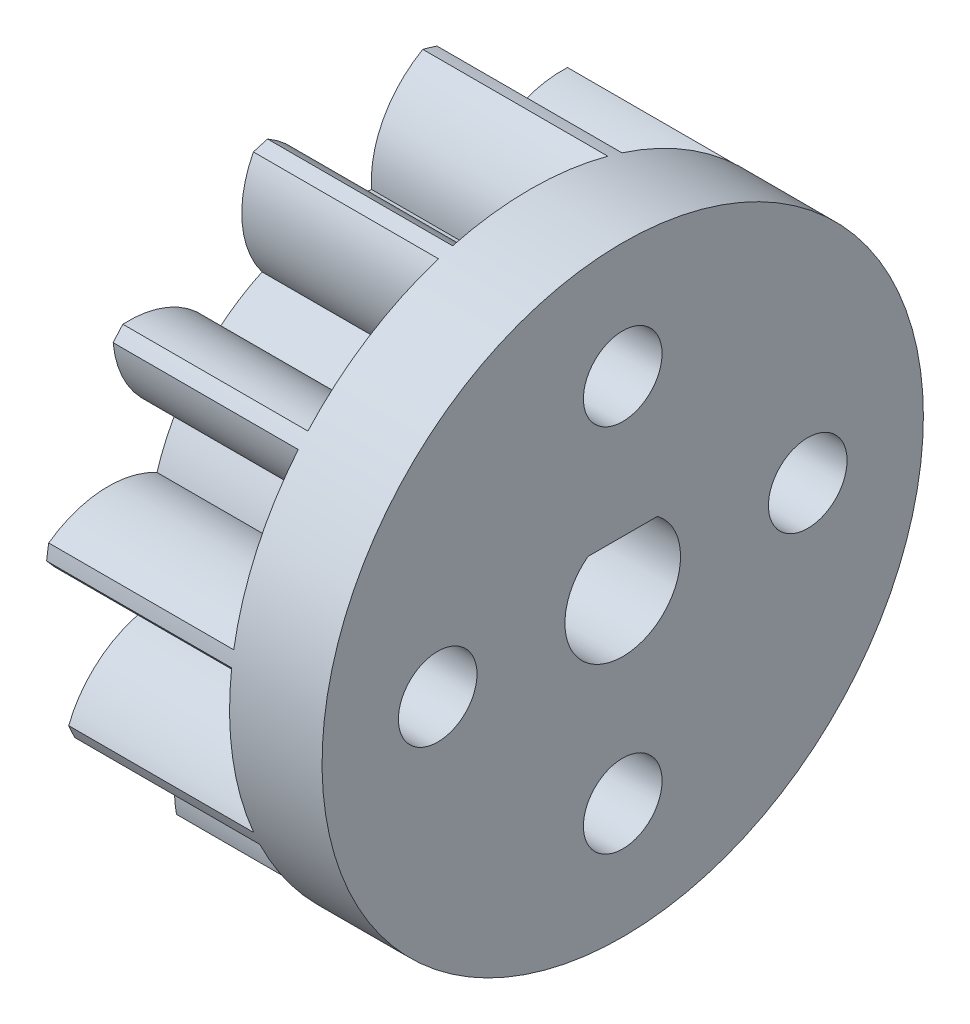
SolidWorks part; units mm, degrees
ref_plane "Plane1" through (0, 0, 0) normal (0, 0, 1) x (1, 0, 0)
ref_plane "Plane2" through (0, 0, 0) normal (0, 1, 0) x (1, 0, 0)
ref_plane "Plane3" through (0, 0, 0) normal (1, 0, 0) x (0, 0, -1)
sketch "HoldingSke" plane through (0, 0, 0) normal (0, 1, 0) x (1, 0, 0)
  line L0 (0, 0) -> (0.4908, -0.0954)
  line L1 (-15, 0) -> (100, 0) construction
  line L2 (0, 0) -> (-2.1039, 2.3779)
  line L3 (0, 0) -> (-11.863, 4.5341)
  line L4 (0, 0) -> (8.4773, 1.6478)
  line L5 (0, 0) -> (-46.8476, -17.4728)
  line L6 (0, 0) -> (-6.6317, -4.4744)
  line L7 (-2.1039, 2.3779) -> (8.6586, 51.2059)
  line L8 (-76.2, 54.61) -> (-76.1, 54.61)
  line L9 (-71.009, 38.7566) -> (-53.1078, 45.2721)
  line L10 (-76.2, 71.12) -> (104.1128, 71.12)
  line L11 (0, 0) -> (-8, 0)
  line L12 (-76.2, 101.6) -> (-76.133, 101.6)
  line L13 (24.9733, 27.94) -> (52.9518, 28.4284)
  line L14 (24.9733, 27.94) -> (24.9743, 27.94)
  line L15 (24.9733, 27.94) -> (100.4006, 29.5858)
  line L16 (-63.627, -2) -> (-12.827, -2)
  circle A0 centre (0, 0) radius 0.4
  circle A1 centre (0, 0) radius 8.499
  circle A2 centre (0, 0) radius 37.5
  circle A3 centre (0, 0) radius 0.4
  dimension "MHD" = 16.998
  dimension "Hub_dia" = 75
  dimension "Bore" = 0.8
  dimension "MBD" = 0.8
  dimension "Num_teeth" = 11
  dimension "Pitch" = 0.5
  dimension "Overall_len" = 50
  dimension "Show_teeth" = 11
  dimension "Thickness" = 8
  dimension "OAL" = 50.0001
  dimension "T_dim" = 0.1
  dimension "Ap" = 20
  dimension "H" = 19.05
  dimension "Pitch_radius" = 180.3128
  dimension "Width" = 8
  dimension "Backlash" = 0.067
  dimension "Addendum_fac" = 1
  dimension "Dedendum_fac" = 1.25
  dimension "Clearance_fac" = 0.25
  dimension "Dedendum_add" = 0.001
  dimension "Module" = 2
sketch "BasProSke" plane through (0, 0, 0) normal (0, 1, 0) x (1, 0, 0)
  line L0 (-10, 0) -> (60, 0) construction
  line L1 (0, 0) -> (0, 13)
  line L2 (0, 0) -> (8, 0)
  line L3 (8, 0) -> (8, 13)
  line L4 (8, 13) -> (0, 13)
  dimension "Thickness" = 8
  dimension "Diameter" = 26
revolve "Base-Revolve" add sketch "BasProSke" angle 360 about L0
sketch "TooCutSke" plane through (0, 0, 0) normal (1, 0, 0) x (0, 0, -1)
  line L1 (0, 0) -> (0, 107) construction
  line L2 (0, 0) -> (-1.6825, 10.8706) construction
  line L3 (0, 0) -> (-6.1442, 20.9251) construction
  line L4 (-1.6825, 10.8706) -> (-3.0721, 10.4626) construction
  arc A0 (1.1399, 8.4222) -> (-1.1399, 8.4222) centre (0, 0) ccw
  arc A1 (3.3871, 12.5773) -> (-3.3871, 12.5773) centre (0, 0) ccw
  circle A2 centre (0, 0) radius 11 construction
  circle A3 centre (0, 0) radius 10.3366 construction
  arc A4 (-1.1399, 8.4222) -> (-3.3871, 12.5773) centre (-5.5288, 8.7337) ccw
  arc A5 (3.3871, 12.5773) -> (1.1399, 8.4222) centre (5.5288, 8.7337) ccw
  dimension "Root_dia" = 16.998
  dimension "Overcut_dia" = 26.0508
  dimension "Pitch_dia" = 22
  dimension "Base_dia" = 20.6732
  dimension "Flank_rad" = 4.4
  dimension "Half_ang" = 16.364
  dimension "Half_CT" = 1.4482
extrude "ToothCut" cut sketch "TooCutSke" along normal through all
fillet "Breaks" [suppressed] radius 0.04
fillet "RootFillets" [suppressed] radius 0.501
pattern_circular "TeethCuts" count 11 every 32.727 about axis through (-10, 0, 0) along (1, 0, 0) of "ToothCut", "RootFillets", "Breaks"
sketch "HubNeaOneSke" plane through (0, 0, 0) normal (-1, 0, 0) x (0, 0, 1)
  circle A0 centre (0, 0) radius 8.499
  dimension "Diameter" = 16.998
extrude "HubNearOne" [suppressed] add sketch "HubNeaOneSke" along normal blind 42.0001
sketch "HubNeaBotSke" plane through (0, 0, 0) normal (-1, 0, 0) x (0, 0, 1)
  circle A0 centre (0, 0) radius 8.499
  dimension "Diameter" = 16.998
extrude "HubNearBoth" [suppressed] add sketch "HubNeaBotSke" along normal blind 21
ref_plane "FarPln" through (8, 0, 0) normal (1, 0, 0) x (0, 0, -1)
sketch "HubFarSke" plane through (8, 0, 0) normal (1, 0, 0) x (0, 0, -1)
  circle A0 centre (0, 0) radius 8.499
  dimension "Diameter" = 16.998
extrude "HubFar" [suppressed] add sketch "HubFarSke" along normal blind 21
sketch "BorSke" plane through (0, 0, 0) normal (1, 0, 0) x (0, 0, -1)
  circle A0 centre (0, 0) radius 0.4
  dimension "Diameter" = 0.8
extrude "Bore" cut sketch "BorSke" along normal mid plane 100.0001
sketch "KeySke" plane through (0, 0, 0) normal (1, 0, 0) x (0, 0, -1)
  line L0 (-0.05, 0) -> (-0.05, 0.5)
  line L1 (-0.05, 0.5) -> (0.05, 0.5)
  line L2 (0.05, 0.5) -> (0.05, 0)
  line L3 (0, 0) -> (0, 34) construction
  line L4 (-0.05, 0) -> (0.05, 0)
  dimension "Offset" = 0.5
  dimension "Width" = 0.1
extrude "Keyway" [suppressed] cut sketch "KeySke" along normal mid plane 100.0001
pattern_circular "Keyway2" [suppressed] count 2 every 90 about axis through (-10, 0, 0) along (1, 0, 0)
sketch "Schizzo2" plane through (8, 0, 0) normal (1, 0, 0) x (0, 0, -1)
  circle A0 centre (0, 0) radius 13
  dimension "D1" = 26
extrude "Estrusione-Estrusione1" add sketch "Schizzo2" along normal blind 4
sketch "Schizzo1" plane through (12, 0, 0) normal (1, 0, 0) x (0, 0, -1)
  line L0 (-1.5, 2) -> (1.5, 2)
  arc A0 (-1.5, 2) -> (1.5, 2) centre (0, 0) ccw
  dimension "D1" = 5
  dimension "D2" = 2
extrude "Taglio-Estrusione1" cut sketch "Schizzo1" against normal blind 14
hole_wizard "Foro per Vite M3-1" positions "Schizzo3" profile "Schizzo4" hole size "M3" standard "DIN"
sketch "Schizzo3" plane through (12, 0, 0) normal (1, 0, 0) x (0, 0, -1)
  circle A0 centre (0, 0) radius 8 construction
  point P3 (0, 8)
  point P5 (8, 0)
  point P7 (0, -8)
  point P9 (-8, 0)
  dimension "D1" = 16
sketch "Schizzo4" plane through (12, 8, 0) normal (0, 1, 0) x (0, 0, -1)
  line L0 (0, 0) -> (0, 4.0215)
  line L1 (0, 4.0215) -> (1.7, 3)
  line L2 (1.7, 3) -> (1.7, 0)
  line L5 (1.7, 0) -> (0, 0)
  line L10 (0, 4.0215) -> (-1.7, 3) construction
  line L11 (0, -6.35) -> (0, 107.95) construction
  dimension "Hole Dia." = 3.4
  dimension "Hole Depth" = 3
  dimension "Drill Angle" = 118
equation "' \"Module@HoldingSke\" = 6.35"
equation "' \"Num_teeth@HoldingSke\" = 12"
equation "' \"Ap@HoldingSke\" =  20"
equation "' \"Ap@HoldingSke\" = 20"
equation "' \"Width@HoldingSke\" = 0.5 * 25.4"
equation "' \"Hub_dia@HoldingSke\"= 1 * 25.4"
equation "' \"Hub_dia@HoldingSke\" = 1 * 25.4"
equation "' \"Overall_len@HoldingSke\" = 1.0 * 25.4"
equation "' \"Bore@HoldingSke\" = 0.75 * 25.4"
equation "' \"T_dim@HoldingSke\" = 0.1 * 25.4"
equation "' \"Width@KeySke\" = 0.25 * 25.4"
equation "' \"Show_teeth@HoldingSke\" = 13"
equation "' \"Backlash@HoldingSke\" = 0.009 * 25.4"
equation "' \"Addendum_fac@HoldingSke\" = 1.0"
equation "' \"Dedendum_fac@HoldingSke\" = 1.25"
equation "' \"Dedendum_add@HoldingSke\" = 0.00005 * 25.4"
equation "' \"Clearance_fac@HoldingSke\" = 0.25"
equation "\"Pitch@HoldingSke\" = 1 / \"Module@HoldingSke\""
equation "\"Overcut_dia@TooCutSke\" = (\"Num_teeth@HoldingSke\" + 2 * \"Addendum_fac@HoldingSke\") / \"Pitch@HoldingSke\" + 0.002 * 25.4"
equation "\"Pitch_dia@TooCutSke\" = \"Num_teeth@HoldingSke\" / \"Pitch@HoldingSke\""
equation "\"Base_dia@TooCutSke\" = \"Num_teeth@HoldingSke\" / \"Pitch@HoldingSke\" * cos((\"Ap@HoldingSke\"  * 3.14159265 / 180))"
equation "\"Root_dia@TooCutSke\" = (\"Num_teeth@HoldingSke\" + 2) / \"Pitch@HoldingSke\" - 2 * (\"Addendum_fac@HoldingSke\" + \"Dedendum_fac@HoldingSke\") / \"Pitch@HoldingSke\" - \"Dedendum_add@HoldingSke\" * 2"
equation "\"Half_ang@TooCutSke\" = 180 / \"Num_teeth@HoldingSke\""
equation "\"Half_CT@TooCutSke\" = \"Num_teeth@HoldingSke\" / \"Pitch@HoldingSke\" * sin((3.14159265 / 2 / \"Num_teeth@HoldingSke\")) / 2 - 7 * \"Backlash@HoldingSke\" / 4"
equation "\"Flank_rad@TooCutSke\" = \"Num_teeth@HoldingSke\" / \"Pitch@HoldingSke\" / 5"
equation "\"Radius@RootFillets\" = \"Clearance_fac@HoldingSke\" / \"Pitch@HoldingSke\" + \"Dedendum_add@HoldingSke\""
equation "\"Break_rad@Breaks\" = 0.02 / \"Pitch@HoldingSke\""
equation "\"Thickness@HoldingSke\" = \"Width@HoldingSke\""
equation "\"OAL@HoldingSke\" = \"Thickness@HoldingSke\""
equation "\"MHD@HoldingSke\" = (\"Num_teeth@HoldingSke\" + 2) / \"Pitch@HoldingSke\" - 2 * (\"Addendum_fac@HoldingSke\" + \"Dedendum_fac@HoldingSke\")  / \"Pitch@HoldingSke\" - \"Dedendum_add@HoldingSke\" * 2"
equation "\"MBD@HoldingSke\" = (\"Num_teeth@HoldingSke\" + 2) / \"Pitch@HoldingSke\" - 2 * (\"Addendum_fac@HoldingSke\" + \"Dedendum_fac@HoldingSke\")  / \"Pitch@HoldingSke\" - \"Dedendum_add@HoldingSke\" * 2 - 0.002 * 25.4"
equation "\"MHD@HoldingSke\" = ((sgn( \"MHD@HoldingSke\" - \"Hub_dia@HoldingSke\" )-1)*( \"MHD@HoldingSke\" - \"Hub_dia@HoldingSke\" ))/-2+ \"Hub_dia@HoldingSke\""
equation "\"MBD@HoldingSke\" = ((sgn( \"MBD@HoldingSke\" - \"Bore@HoldingSke\" )-1)*( \"MBD@HoldingSke\" - \"Bore@HoldingSke\" ))/-2+ \"Bore@HoldingSke\""
equation "\"OAL@HoldingSke\" = ((sgn( \"OAL@HoldingSke\" - \"Overall_len@HoldingSke\" )+1)*( \"OAL@HoldingSke\" - \"Overall_len@HoldingSke\" ))/2 + \"Overall_len@HoldingSke\" + 0.000002 * 25.4"
equation "\"Num_teeth@TeethCuts\" = int( \"Show_teeth@HoldingSke\" ) + 1"
equation "\"Num_teeth@TeethCuts\" = ((sgn( \"Num_teeth@TeethCuts\" - \"Num_teeth@HoldingSke\" )-1)*( \"Num_teeth@TeethCuts\" - \"Num_teeth@HoldingSke\" ))/-2+ \"Num_teeth@HoldingSke\""
equation "\"Num_teeth@TeethCuts\" = ((sgn( \"Num_teeth@TeethCuts\" - 2.0)+1)*( \"Num_teeth@TeethCuts\" - 2.0))/2 +2.0"
equation "\"Angle@TeethCuts\" = 360.0 / \"Num_teeth@HoldingSke\""
equation "\"Diameter@BasProSke\" = (\"Num_teeth@HoldingSke\" + 2 * \"Addendum_fac@HoldingSke\") / \"Pitch@HoldingSke\""
equation "\"Thickness@BasProSke\"  = \"Thickness@HoldingSke\""
equation "' \"Fillet_rad@BasProSke\" =  \"Thickness@HoldingSke\" * 0.05"
equation "' \"Fillet_rad@BasProSke\" = \"Thickness@HoldingSke\" * 0.05"
equation "\"MHD@HoldingSke\" = ((sgn( \"MHD@HoldingSke\" - \"Root_dia@TooCutSke\" )-1)*( \"MHD@HoldingSke\" - \"Root_dia@TooCutSke\" ))/-2+ \"Root_dia@TooCutSke\""
equation "\"Diameter@HubNeaOneSke\" = \"MHD@HoldingSke\""
equation "\"Length@HubNearOne\" = \"OAL@HoldingSke\" - \"Thickness@BasProSke\""
equation "\"Diameter@HubNeaBotSke\" = \"MHD@HoldingSke\""
equation "\"Length@HubNearBoth\" = ( \"OAL@HoldingSke\" - \"Thickness@BasProSke\" ) / 2.0"
equation "\"Thickness@FarPln\" = \"Thickness@BasProSke\""
equation "\"Diameter@HubFarSke\" = \"MHD@HoldingSke\""
equation "\"Length@HubFar\" = ( \"OAL@HoldingSke\" - \"Thickness@BasProSke\" ) / 2.0"
equation "\"Diameter@BorSke\" = \"MBD@HoldingSke\""
equation "\"D1@Bore\" = \"OAL@HoldingSke\" * 2.0"
equation "\"D1@Keyway\" = \"OAL@HoldingSke\" * 2.0"
equation "\"Offset@KeySke\" = \"T_dim@HoldingSke\" + \"MBD@HoldingSke\" / 2.0"
